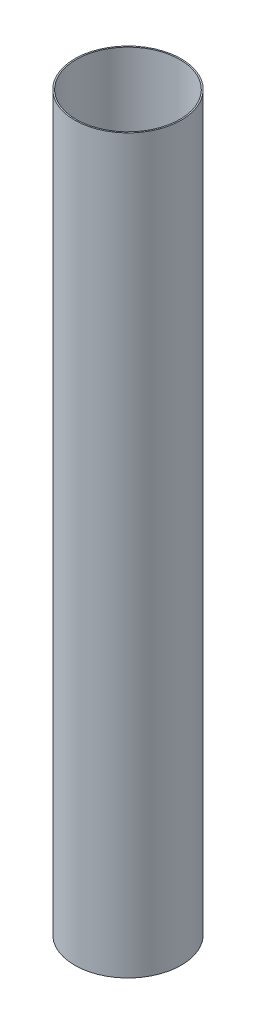
SolidWorks part; units mm, degrees
material "Corrugated Paper"
ref_plane "Front Plane" through (0, 0, 0) normal (0, 0, 1) x (1, 0, 0)
ref_plane "Top Plane" through (0, 0, 0) normal (0, 1, 0) x (1, 0, 0)
ref_plane "Right Plane" through (0, 0, 0) normal (1, 0, 0) x (0, 0, -1)
sketch "Sketch2" plane through (0, 0, 0) normal (0, 1, 0) x (1, 0, 0)
  circle A0 centre (0, 0) radius 40
  circle A1 centre (0, 0) radius 39
  dimension "D1" = 80
  dimension "D2" = 78
extrude "body" add sketch "Sketch2" along normal blind 550
equation "\"paper_size\" = 600mm"
equation "\"cb_roll_d_outer\" = 80mm"
equation "\"cb_roll_d_inner\" = 78mm"
equation "\"D1@body\"= \"paper_size\" - \"attached_len\" + 20"
equation "\"attached_len\" = 70mm"
equation "\"helper_d\" = 86mm"
equation "\"outer_d\" = 106mm"
equation "\"spring_l_max\" = 25mm"
equation "\"spring_l_min\" = 10mm"
